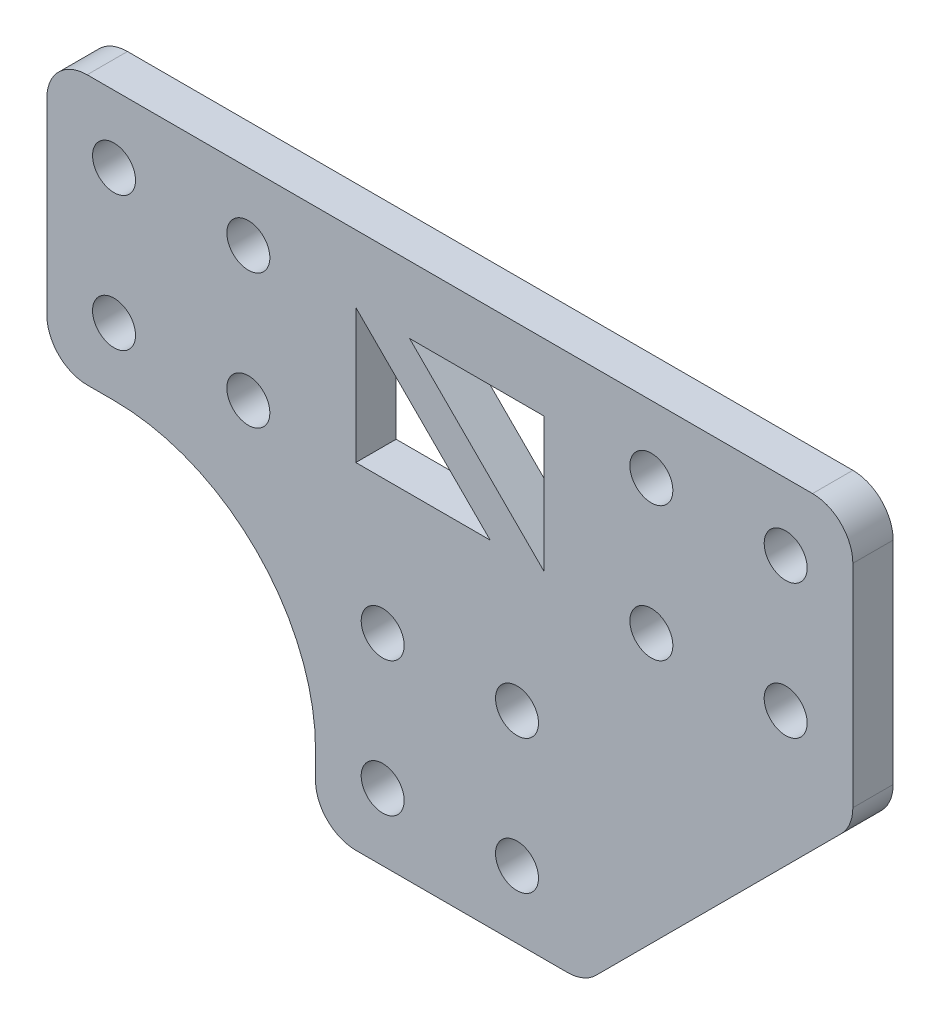
SolidWorks part; units mm, degrees
ref_plane "前视基准面" through (0, 0, 0) normal (0, 0, 1) x (1, 0, 0)
ref_plane "上视基准面" through (0, 0, 0) normal (0, 1, 0) x (1, 0, 0)
ref_plane "右视基准面" through (0, 0, 0) normal (1, 0, 0) x (0, 0, -1)
other "Configuration Table"
sketch "草图1" plane through (0, 0, 0) normal (0, 0, 1) x (1, 0, 0)
  line L0 (0, 0) -> (60, 0)
  line L1 (60, 0) -> (60, -20)
  line L2 (60, -20) -> (40, -40)
  line L3 (40, -40) -> (20, -40)
  line L5 (0, -20) -> (0, 0)
  line L6 (30, 0) -> (30, -40) construction
  line L7 (0, -10) -> (30, -10) construction
  line L8 (10, -10) -> (10, 0) construction
  line L9 (30, -30) -> (20, -30) construction
  line L10 (23, -5) -> (23, -15)
  line L11 (23, -15) -> (33, -15)
  line L12 (33, -15) -> (23, -5)
  line L13 (27, -5) -> (37, -5)
  line L14 (37, -5) -> (37, -15)
  line L15 (37, -15) -> (27, -5)
  line L19 (0, -20) -> (20, -20)
  line L20 (20, -20) -> (20, -40)
  circle A0 centre (5, -5) radius 1.6
  circle A1 centre (15, -5) radius 1.6
  circle A2 centre (15, -15) radius 1.6
  circle A3 centre (5, -15) radius 1.6
  circle A4 centre (55, -15) radius 1.6
  circle A5 centre (45, -15) radius 1.6
  circle A6 centre (45, -5) radius 1.6
  circle A7 centre (55, -5) radius 1.6
  circle A8 centre (25, -35) radius 1.6
  circle A9 centre (35, -35) radius 1.6
  circle A10 centre (35, -25) radius 1.6
  circle A11 centre (25, -25) radius 1.6
  point P45 (20, -30)
  dimension "D8" = 3.2
  dimension "D11" = 3.2
  dimension "D1" = 20
  dimension "D2" = 20
  dimension "D3" = 20
  dimension "D4" = 60
  dimension "D5" = 40
  dimension "D6" = 10
  dimension "D7" = 10
  dimension "D9" = 5
  dimension "D10" = 5
  dimension "D12" = 5
  dimension "D13" = 5
  dimension "D14" = 10
  dimension "D15" = 10
  dimension "D16" = 10
  dimension "D17" = 10
  dimension "D18" = 7
  dimension "D19" = 7
extrude "凸台-拉伸1" add sketch "草图1" along normal blind 3
fillet "圆角1" radius 3 6 edges at (60, -20, 1.5) (40, -40, 1.5) (60, 0, 1.5) (0, 0, 1.5) (20, -40, 1.5) (0, -20, 1.5)
fillet "圆角2" radius 15 1 edges at (20, -20, 1.5)
